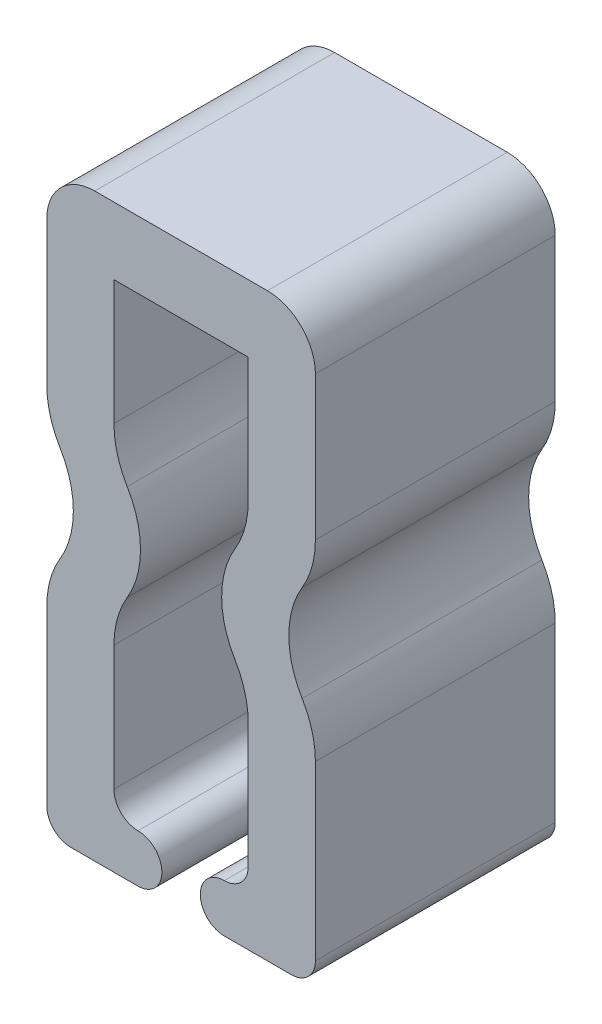
SolidWorks part; units mm, degrees
ref_plane "Front Plane" through (0, 0, 0) normal (0, 0, 1) x (1, 0, 0)
ref_plane "Top Plane" through (0, 0, 0) normal (0, 1, 0) x (1, 0, 0)
ref_plane "Right Plane" through (0, 0, 0) normal (1, 0, 0) x (0, 0, -1)
sketch "DualPropShadow" plane through (0, 0, 0) normal (0, 0, 1) x (1, 0, 0)
  line L0 (-1.2, 1.2) -> (0, 3.2)
  line L1 (-1.2, -1.2) -> (1.2, -1.2)
  line L2 (-1.2, -1.2) -> (-1.2, 1.2)
  line L3 (-1.2, 1.2) -> (1.2, 1.2) construction
  line L4 (1.2, -1.2) -> (1.2, 1.2)
  line L5 (-1.2, -1.2) -> (1.2, 1.2) construction
  line L6 (-1.2, 1.2) -> (1.2, -1.2) construction
  line L7 (0, 3.2) -> (1.2, 1.2)
  line L8 (0, 5.2) -> (0, 1.2) construction
  line L9 (-1000, 3.2) -> (49000, 3.2) construction
  line L10 (-1.2, 5.2) -> (1.2, 7.6) construction
  line L11 (-1.2, 7.6) -> (1.2, 5.2) construction
  line L12 (-1.2, 5.2) -> (1.2, 5.2) construction
  line L13 (0, 3.2) -> (1.2, 5.2)
  line L14 (1.2, 7.6) -> (1.2, 5.2)
  line L15 (-1.2, 7.6) -> (-1.2, 5.2)
  line L16 (-1.2, 7.6) -> (1.2, 7.6)
  line L17 (-1.2, 5.2) -> (0, 3.2)
  point P0 (0, 0)
  point P6 (1.2, 0)
  point P16 (0, 6.4)
  point P17 (-1.2, 5.2)
  dimension "D1" = 2.4
  dimension "D2" = 4.4
  dimension "D3" = 2.4
sketch "Sketch2" plane through (0, 0, 0) normal (0, 0, 1) x (1, 0, 0)
  line L0 (-1.2, -1.2) -> (-1.2, 1.2) construction
  line L1 (-1.2, -1.2) -> (1.2, -1.2) construction
  line L2 (1.2, -1.2) -> (1.2, 1.2) construction
  line L3 (0, 3.2) -> (1.2, 1.2) construction
  line L4 (-1.2, 1.2) -> (0, 3.2) construction
  line L5 (1.2, 7.6) -> (1.2, 5.2) construction
  line L6 (0, 3.2) -> (1.2, 5.2) construction
  line L7 (-1.2, 5.2) -> (0, 3.2) construction
  line L8 (-1.2, 7.6) -> (-1.2, 5.2) construction
  line L9 (-1.2, 7.6) -> (1.2, 7.6) construction
  line L10 (-1.2, -1.2) -> (-1.2, 1.2) construction
  line L11 (-1.2, -1.2) -> (1.2, -1.2) construction
  line L12 (1.2, -1.2) -> (1.2, 1.2) construction
  line L13 (0, 3.2) -> (1.2, 1.2) construction
  line L14 (-1.2, 1.2) -> (0, 3.2) construction
  line L15 (1.2, 7.6) -> (1.2, 5.2) construction
  line L16 (0, 3.2) -> (1.2, 5.2) construction
  line L17 (-1.2, 5.2) -> (0, 3.2) construction
  line L18 (-1.2, 7.6) -> (-1.2, 5.2) construction
  line L19 (-1.2, 7.6) -> (1.2, 7.6) construction
  line L20 (0, -996.8) -> (0, 49003.2) construction
  line L21 (-1000, 3.2) -> (49000, 3.2) construction
  line L22 (-1.4, 7.8) -> (1.4, 7.8)
  line L23 (-1.2, 7.8) -> (-1.2, 7.6) construction
  line L24 (-1.4, 7.8) -> (-1.4, 5.2)
  line L25 (-1.4, -1.4) -> (-1.4, 1.2)
  line L26 (-1.2, 7.6) -> (-1.4, 7.6) construction
  line L27 (-0.846, 3.2) -> (-0.846, 4.6101) construction
  line L28 (-1.4, 5.2) -> (-1.4, 1.2) construction
  line L29 (-1.123, 4.2) -> (-0.523, 3.2) construction
  line L30 (1.8, 9.2) -> (-1.8, 9.2)
  line L31 (-1.4, 5.2) -> (-1.4, 1.2) construction
  line L32 (-1.4, -1.4) -> (1.4, -1.4) construction
  line L33 (1.4, 7.8) -> (1.4, 5.2) construction
  line L34 (-1.4, 7.8) -> (1.4, 7.8) construction
  line L35 (1.4, -1.4) -> (1.4, 1.2) construction
  line L36 (-2.8, 8.2) -> (-2.8, 5.2)
  line L37 (-1.4, 9.2) -> (-1.4, 7.8) construction
  line L38 (-1.4, 7.8) -> (-2.8, 7.8) construction
  line L39 (2.8, 8.2) -> (2.8, 5.2)
  line L40 (-0.4, -2.4) -> (-0.4, -1.2) construction
  line L41 (-1.2, 0) -> (-0.4, 0) construction
  line L42 (-0.4, 0) -> (0.4, 0) construction
  line L43 (0.4, 0) -> (1.2, 0) construction
  line L44 (-2.8, 1.2) -> (-2.8, -2.4)
  line L45 (-2.3, -2.9) -> (-0.9, -2.9)
  line L46 (1.4, 7.8) -> (1.4, 5.2)
  line L47 (1.4, 5.2) -> (1.4, 1.2) construction
  line L48 (2.3, -2.9) -> (0.9, -2.9)
  line L49 (1.4, -1.4) -> (1.4, 1.2)
  line L50 (2.8, 1.2) -> (2.8, -2.4)
  line L51 (-1.4, 8.5) -> (0, 8.5) construction
  arc A0 (-1.4, 5.2) -> (-1.123, 4.2) centre (0.5437, 5.2) ccw
  arc A1 (-1.123, 4.2) -> (-1.123, 2.2) centre (-2.7897, 3.2) cw
  arc A2 (-1.4, 1.2) -> (-1.123, 2.2) centre (0.5437, 1.2) cw
  arc A3 (-2.8, 5.2) -> (-2.523, 4.2) centre (-0.8563, 5.2) ccw
  arc A4 (-2.8, 1.2) -> (-2.523, 2.2) centre (-0.8563, 1.2) cw
  arc A5 (-2.523, 4.2) -> (-2.523, 2.2) centre (-4.1897, 3.2) cw
  arc A6 (-2.8, 8.2) -> (-1.8, 9.2) centre (-1.8, 8.2) cw
  arc A7 (-1.4, -1.4) -> (-0.9, -1.9) centre (-0.9, -1.4) ccw
  arc A8 (-0.9, -1.9) -> (-0.4, -2.4) centre (-0.9, -2.4) cw
  arc A9 (-2.8, -2.4) -> (-2.3, -2.9) centre (-2.3, -2.4) ccw
  arc A10 (-0.4, -2.4) -> (-0.9, -2.9) centre (-0.9, -2.4) cw
  arc A11 (2.8, 8.2) -> (1.8, 9.2) centre (1.8, 8.2) ccw
  arc A12 (1.4, 5.2) -> (1.123, 4.2) centre (-0.5437, 5.2) cw
  arc A13 (2.8, -2.4) -> (2.3, -2.9) centre (2.3, -2.4) cw
  arc A14 (2.8, 5.2) -> (2.523, 4.2) centre (0.8563, 5.2) cw
  arc A15 (2.8, 1.2) -> (2.523, 2.2) centre (0.8563, 1.2) ccw
  arc A16 (2.523, 4.2) -> (2.523, 2.2) centre (4.1897, 3.2) ccw
  arc A17 (1.4, 1.2) -> (1.123, 2.2) centre (-0.5437, 1.2) ccw
  arc A18 (1.123, 4.2) -> (1.123, 2.2) centre (2.7897, 3.2) ccw
  arc A19 (0.4, -2.4) -> (0.9, -2.9) centre (0.9, -2.4) ccw
  arc A20 (1.4, -1.4) -> (0.9, -1.9) centre (0.9, -1.4) cw
  arc A21 (0.9, -1.9) -> (0.4, -2.4) centre (0.9, -2.4) ccw
  point P38 (-0.9, -1.4)
  point P47 (-1.4, -1.4)
  point P58 (-1.2, -0.3352)
  point P60 (-1.2, 0)
  point P62 (0, 0)
  point P66 (0, 9.2)
  point P67 (0, 7.8)
  point P94 (-0.8, 1.2)
  dimension "D3" = 1
  dimension "D4" = 0.5
  dimension "D2" = 1.4
  dimension "D1" = 0.2
extrude "Boss-Extrude1" add sketch "Sketch2" along normal blind 5
equation "\"prop_height\"= 4.4mm"
equation "\"prop_th\"= 2.4mm"
equation "\"prop_indent_height\"= 2.4mm"
equation "\"prop_radius\"= 42mm"
equation "\"D1@DualPropShadow\" = \"prop_indent_height\""
equation "\"D2@DualPropShadow\" = \"prop_height\""
equation "\"D3@DualPropShadow\" = \"prop_th\""
